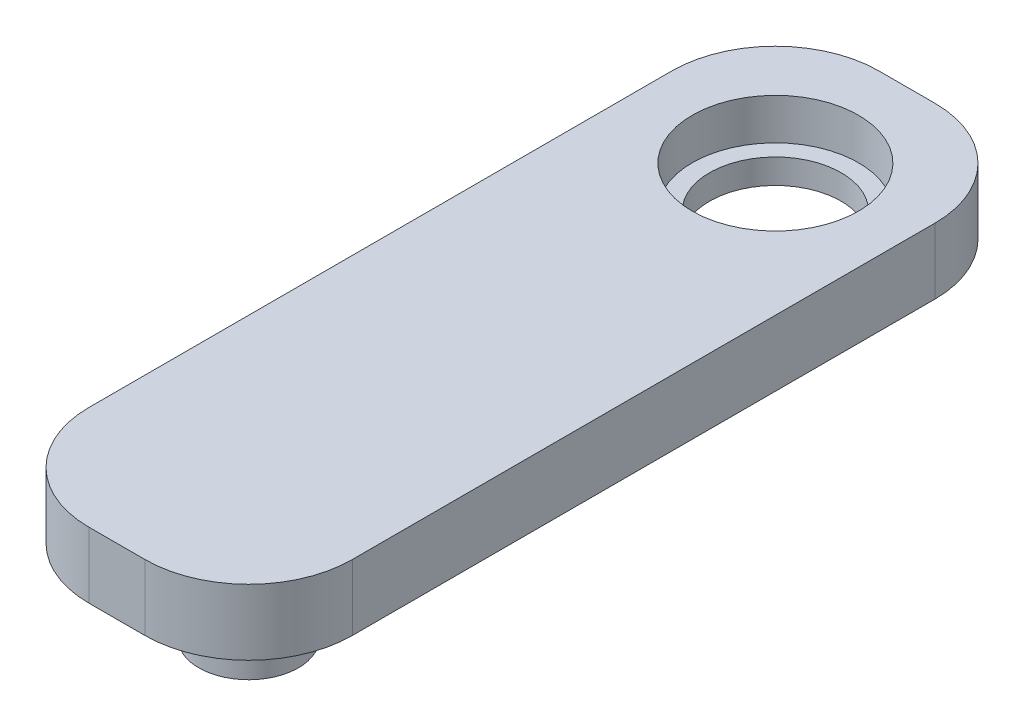
SolidWorks part; units mm, degrees
ref_plane "Front Plane" through (0, 0, 0) normal (0, 0, 1) x (1, 0, 0)
ref_plane "Top Plane" through (0, 0, 0) normal (0, 1, 0) x (1, 0, 0)
ref_plane "Right Plane" through (0, 0, 0) normal (1, 0, 0) x (0, 0, -1)
sketch "Sketch1" plane through (0, 0, 0) normal (0, 1, 0) x (1, 0, 0)
  line L1 (0, 0) -> (25.4, 0)
  line L2 (0, 0) -> (0, 76.2)
  line L3 (0, 76.2) -> (25.4, 76.2)
  line L4 (25.4, 0) -> (25.4, 76.2)
  dimension "D1" = 76.2
  dimension "D2" = 25.4
extrude "Boss-Extrude1" add sketch "Sketch1" along normal blind 6.35
sketch "Sketch5" plane through (0, 6.35, 0) normal (0, 1, 0) x (1, 0, 0)
  line L0 (0, 76.2) -> (0, 0) construction
  line L1 (25.4, 0) -> (25.4, 76.2) construction
  line L2 (25.4, 76.2) -> (0, 76.2) construction
  circle A0 centre (12.7, 63.5) radius 8.0169
  dimension "D3" = 16.0337
  dimension "D1" = 25.4
  dimension "D2" = 12.7
extrude "Cut-Extrude1" cut sketch "Sketch5" against normal blind 3.9688
sketch "Sketch6" plane through (0, 2.3812, 0) normal (0, 1, 0) x (1, 0, 0)
  circle A0 centre (12.7, 63.5) radius 6.35
  dimension "D1" = 12.7
extrude "Cut-Extrude2" cut sketch "Sketch6" against normal through all
sketch "Sketch7" plane through (0, 6.35, 0) normal (0, 1, 0) x (1, 0, 0)
  line L0 (25.4, 0) -> (25.4, 76.2) construction
  line L5 (0, 0) -> (25.4, 0) construction
  circle A0 centre (12.7, 12.7) radius 5.5563
  dimension "D3" = 11.1125
  dimension "D1" = 12.7
  dimension "D2" = 12.7
extrude "Boss-Extrude2" add sketch "Sketch7" against normal blind 4 from surface at -6.35 starting at face at (12.7, 0, -57.15)
sketch "Sketch8" plane through (0, -4, 0) normal (0, -1, 0) x (1, 0, 0)
  circle A0 centre (12.7, -12.7) radius 4.805
  circle A1 centre (12.7, -12.7) radius 5.5563 construction
  dimension "D1" = 9.61
  dimension "D2" = 0
extrude "Boss-Extrude3" add sketch "Sketch8" along normal blind 4
fillet "Fillet1" radius 10 4 edges at (0, 3.175, 0) (25.4, 3.175, 0) (0, 3.175, -76.2) (25.4, 3.175, -76.2)
